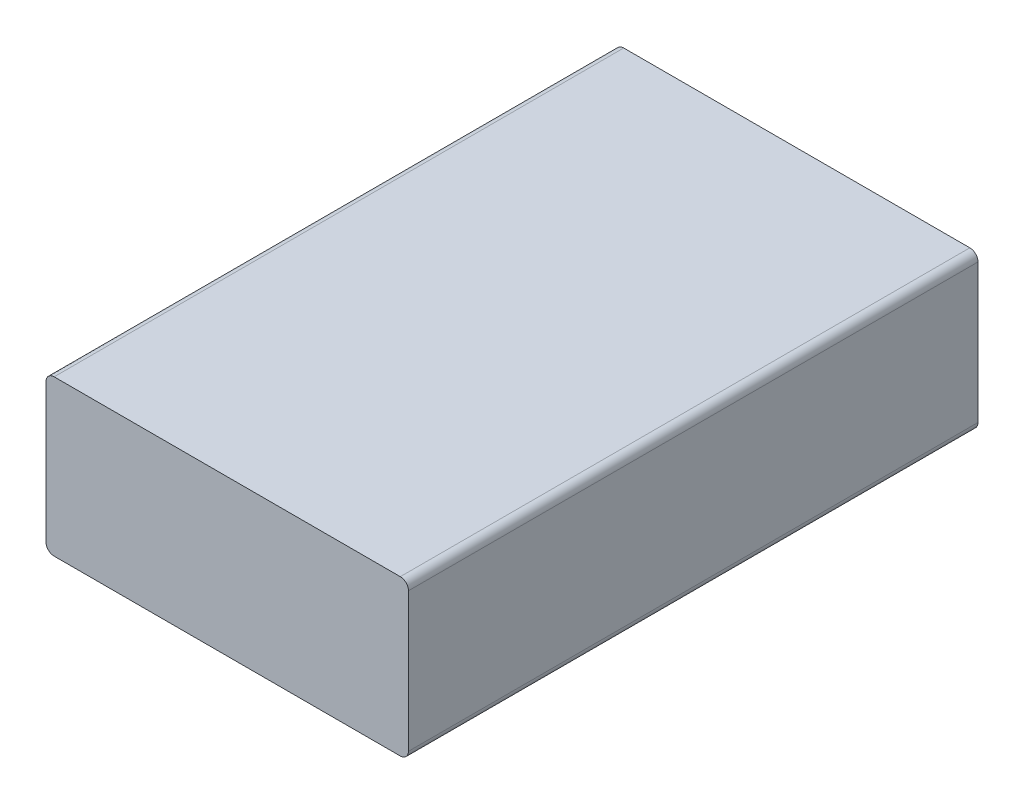
SolidWorks part; units mm, degrees
ref_plane "Front Plane" through (0, 0, 0) normal (0, 0, 1) x (1, 0, 0)
ref_plane "Top Plane" through (0, 0, 0) normal (0, 1, 0) x (1, 0, 0)
ref_plane "Right Plane" through (0, 0, 0) normal (1, 0, 0) x (0, 0, -1)
sketch "Sketch1" plane through (0, 0, 0) normal (0, 0, 1) x (1, 0, 0)
  line L1 (-44.45, -19.05) -> (44.45, -19.05)
  line L2 (-44.45, -19.05) -> (-44.45, 19.05)
  line L3 (-44.45, 19.05) -> (44.45, 19.05)
  line L4 (44.45, -19.05) -> (44.45, 19.05)
  line L5 (-44.45, -19.05) -> (44.45, 19.05) construction
  line L6 (-44.45, 19.05) -> (44.45, -19.05) construction
  point P0 (0, 0)
  dimension "D1" = 38.1
  dimension "D2" = 88.9
extrude "Boss-Extrude1" add sketch "Sketch1" along normal blind 139.7
fillet "Fillet1" radius 2 4 edges at (-44.45, 19.05, 69.85) (44.45, 19.05, 69.85) (44.45, -19.05, 69.85) (-44.45, -19.05, 69.85)
other "2x4<1>"
